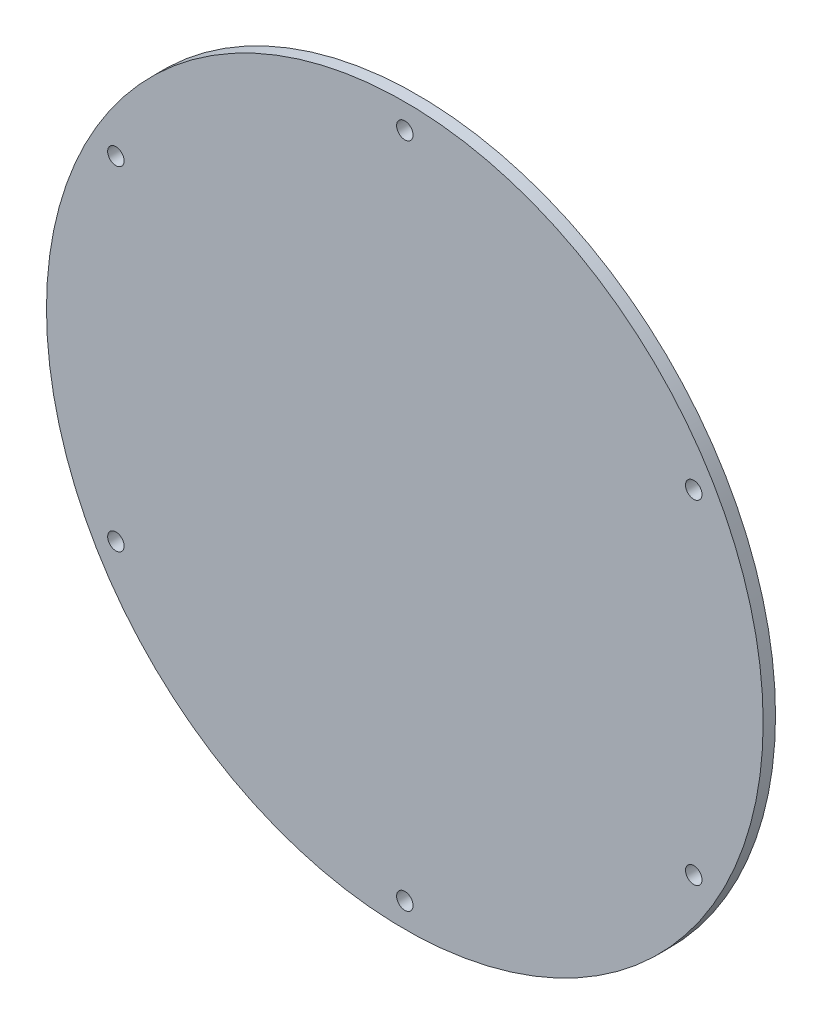
SolidWorks part; units mm, degrees
ref_plane "Front Plane" through (0, 0, 0) normal (0, 0, 1) x (1, 0, 0)
ref_plane "Top Plane" through (0, 0, 0) normal (0, 1, 0) x (1, 0, 0)
ref_plane "Right Plane" through (0, 0, 0) normal (1, 0, 0) x (0, 0, -1)
sketch "Sketch1" plane through (0, 0, 0) normal (0, 0, 1) x (1, 0, 0)
  line L0 (0, 174) -> (0, 162) construction
  circle A0 centre (0, 0) radius 174
  circle A1 centre (0, 162) radius 4
  circle A2 centre (140.2961, 81) radius 4
  circle A3 centre (140.2961, -81) radius 4
  circle A4 centre (0, -162) radius 4
  circle A5 centre (-140.2961, -81) radius 4
  circle A6 centre (-140.2961, 81) radius 4
  point P19 (0, 0)
  dimension "D1" = 348
  dimension "D3" = 8
  dimension "D2" = 12
  dimension "D4" = 6
extrude "Boss-Extrude1" add sketch "Sketch1" along normal blind 6
equation "\"acTubeOD\"= 300mm"
equation "\"acTubeThickness\"= 3mm"
equation "\"acTubeLength\"= 300mm"
equation "\"threadedRodDiam\"= 8mm"
equation "\"flange width\"= 24mm"
equation "\"D1@Sketch1\"=\"acTubeOD\" + \"flange width\"*2"
